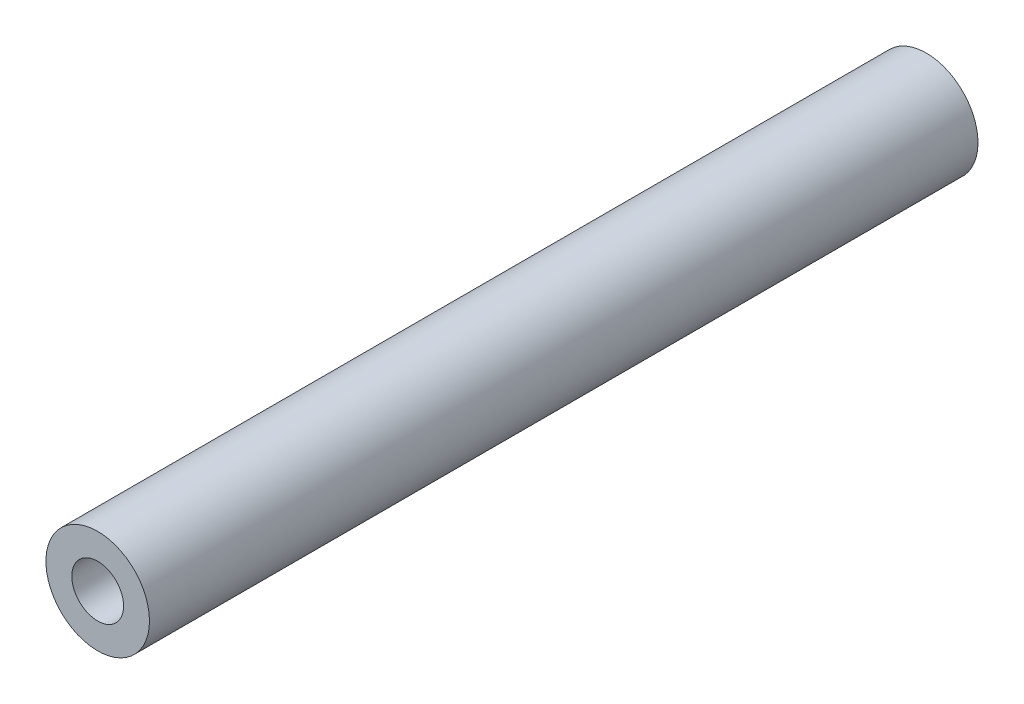
SolidWorks part; units mm, degrees
material "锻制红铜"
ref_plane "前视基准面" through (0, 0, 0) normal (0, 0, 1) x (1, 0, 0)
ref_plane "上视基准面" through (0, 0, 0) normal (0, 1, 0) x (1, 0, 0)
ref_plane "右视基准面" through (0, 0, 0) normal (1, 0, 0) x (0, 0, -1)
sketch "草图1" plane through (0, 0, 0) normal (0, 0, 1) x (1, 0, 0)
  circle A0 centre (0, 0) radius 2
  circle A1 centre (0, 0) radius 4
  dimension "D1" = 8
  dimension "D2" = 4
extrude "凸台-拉伸1" add sketch "草图1" along normal mid plane 64
